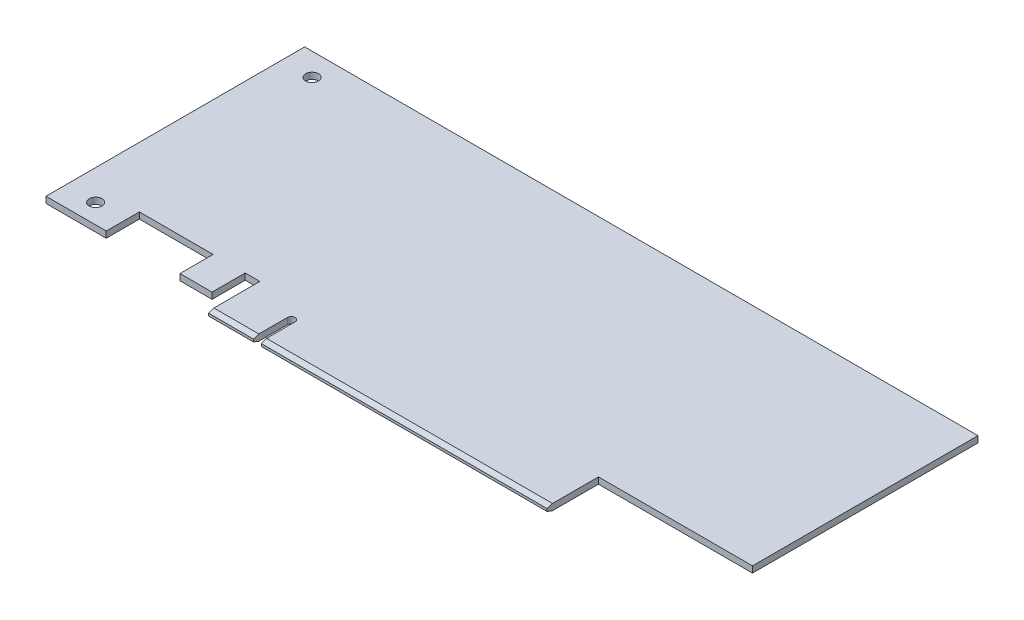
SolidWorks part; units mm, degrees
ref_plane "前视基准面" through (0, 0, 0) normal (0, 0, 1) x (1, 0, 0)
ref_plane "上视基准面" through (0, 0, 0) normal (0, 1, 0) x (1, 0, 0)
ref_plane "右视基准面" through (0, 0, 0) normal (1, 0, 0) x (0, 0, -1)
other "Configuration Table"
sketch "草图1" plane through (0, 0, 0) normal (0, 1, 0) x (1, 0, 0)
  line L0 (-7.5, -4.85) -> (-7.5, 71.7997) construction
  line L1 (-7.5, -4.85) -> (7.5, -4.85)
  line L2 (-7.5, -4.85) -> (-7.5, 4.85)
  line L3 (-7.5, 4.85) -> (7.5, 4.85) construction
  line L4 (7.5, -4.85) -> (7.5, 4.85) construction
  line L5 (-7.5, -4.85) -> (7.5, 4.85) construction
  line L6 (-7.5, 4.85) -> (7.5, -4.85) construction
  line L11 (37.5, 3.4) -> (33.85, 3.4)
  line L12 (25.85, 3.4) -> (7.5, 3.4)
  line L13 (-7.5, 59.55) -> (160.15, 59.55)
  line L18 (121.8, 3.4) -> (160.15, 3.4)
  line L19 (7.5, 3.4) -> (7.5, -4.85)
  line L20 (160.15, 59.55) -> (160.15, 3.4)
  line L21 (-7.5, 59.55) -> (5.2, 59.55)
  line L22 (-7.5, 59.55) -> (-7.5, 48.85)
  line L23 (-7.5, 48.85) -> (5.2, 48.85) construction
  line L24 (5.2, 59.55) -> (5.2, 48.85) construction
  line L25 (49.65, 59.55) -> (49.65, -12.3168) construction
  line L26 (0, -4.85) -> (0, 59.55) construction
  line L27 (-7.5, -9.35) -> (103.0968, -9.35) construction
  line L28 (-7.5, 48.85) -> (-7.5, 4.85)
  line L30 (25.85, -4.85) -> (33.85, -4.85)
  line L31 (25.85, -4.85) -> (25.85, 3.4)
  line L32 (25.85, 3.4) -> (33.85, 3.4) construction
  line L33 (33.85, -4.85) -> (33.85, 3.4)
  line L35 (37.5, 3.4) -> (37.5, -9.35)
  line L36 (37.5, -9.35) -> (48.7, -9.35)
  line L37 (48.7, -0.95) -> (48.7, -9.35)
  line L39 (50.6, -0.95) -> (50.6, -9.35)
  line L40 (50.6, -9.35) -> (121.8, -9.35)
  line L41 (121.8, 3.4) -> (121.8, -9.35)
  circle A0 centre (0, 0) radius 1.59
  circle A1 centre (0, 53.9) radius 1.59
  arc A2 (50.6, -0.95) -> (48.7, -0.95) centre (49.65, -0.95) ccw
  dimension "D1" = 53.9
  dimension "D2" = 68.9
  dimension "D11" = 12.15
  dimension "D12" = 1.9
  dimension "D16" = 15
  dimension "D3" = 5.2
  dimension "D4" = 5.05
  dimension "D5" = 49.65
  dimension "D6" = 167.65
  dimension "D7" = 4.85
  dimension "D8" = 4.5
  dimension "D9" = 11.65
  dimension "D10" = 8.4
  dimension "D13" = 0
  dimension "D14" = 72.15
  dimension "D15" = 3.65
extrude "凸台-拉伸1" add sketch "草图1" along normal blind 1.57 contours A2 L39 L40 L41 L18 L20 L13 L22 L28 L2 L1 L19 L12 L31 L30 L33 L11 L35 L36 L37 A1 A0
sketch "草图2" plane through (121.8, 0, 0) normal (1, 0, 0) x (0, 0, -1)
  line L0 (-8.05, 1.57) -> (-8.05, 0) construction
  line L1 (3.4, 1.57) -> (-9.35, 1.57) construction
  line L2 (3.4, 0) -> (-9.35, 0) construction
  line L3 (-9.35, 1.57) -> (-9.35, 0) construction
  line L4 (-8.05, 1.57) -> (-9.35, 1.0968)
  line L5 (-9.35, 1.0968) -> (-9.35, 0.4732)
  line L6 (-9.35, 0.4732) -> (-8.05, 0)
  line L7 (-8.05, 0) -> (-9.35, 0)
  line L8 (-9.35, 0) -> (-9.35, 1.57)
  line L9 (-9.35, 1.57) -> (-8.05, 1.57)
  line M11 (-9.35, 0) -> (3.4, 0)
  line M13 (3.4, 1.57) -> (-9.35, 1.57)
  line M14 (-9.35, 1.57) -> (-9.35, 0)
  dimension "D1" = 1.3
  dimension "D2" = 20
  dimension "D3" = 160
extrude "切除-拉伸1" cut sketch "草图2" against normal blind 84.57 contours L4 M13 M14 | L6 M14 M11
